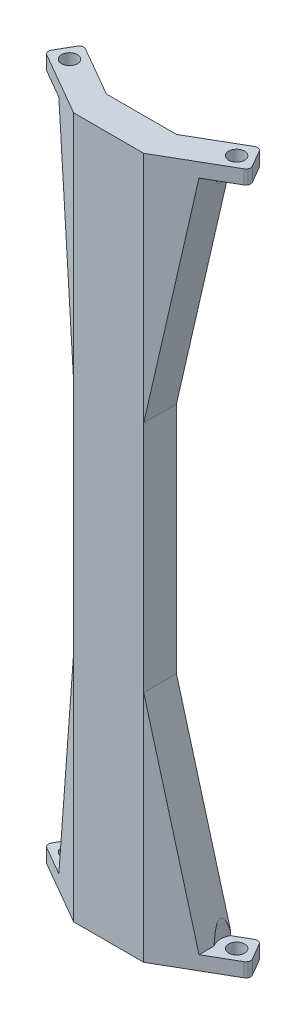
SolidWorks part; units mm, degrees
ref_plane "Front Plane" through (0, 0, 0) normal (0, 0, 1) x (1, 0, 0)
ref_plane "Top Plane" through (0, 0, 0) normal (0, 1, 0) x (1, 0, 0)
ref_plane "Right Plane" through (0, 0, 0) normal (1, 0, 0) x (0, 0, -1)
sketch "Sketch2" plane through (0, 0, 0) normal (0, 0, 1) x (1, 0, 0)
  line L1 (-7.5, -75) -> (7.5, -75)
  line L2 (-7.5, -75) -> (-7.5, 75)
  line L3 (-7.5, 75) -> (7.5, 75)
  line L4 (7.5, -75) -> (7.5, 75)
  line L5 (-7.5, -75) -> (7.5, 75) construction
  line L6 (-7.5, 75) -> (7.5, -75) construction
  point P0 (0, 0)
  dimension "D1" = 150
  dimension "D2" = 15
extrude "Boss-Extrude1" add sketch "Sketch2" along normal mid plane 7
sketch "Sketch3" plane through (0, -75, 0) normal (0, -1, 0) x (1, 0, 0)
  line L0 (-7.5, 3.5) -> (-22.0059, -4.875)
  line L1 (-22.0059, -4.875) -> (-18.9748, -10.125)
  line L2 (-18.9748, -10.125) -> (-7.5, -3.5)
  line L3 (7.5, 3.5) -> (22.0059, -4.875)
  line L4 (22.0059, -4.875) -> (18.9748, -10.125)
  line L5 (18.9748, -10.125) -> (7.5, -3.5)
  line L6 (-7.5, 3.5) -> (-7.5, -3.5) construction
  line L7 (7.5, 3.5) -> (7.5, -3.5) construction
  line L8 (-7.5, 3.5) -> (-7.5, -3.5)
  line L9 (7.5, 3.5) -> (7.5, -3.5)
  line L10 (-20.4904, -7.5) -> (-7.5, 0) construction
  dimension "D1" = 60
  dimension "D2" = 15
  dimension "D3" = 60
extrude "Boss-Extrude2" add sketch "Sketch3" against normal up to surface (150 mm away) up to face at (0, 75, 0)
sketch "Sketch5" plane through (0, 0, 3.5) normal (0, 0, 1) x (1, 0, 0)
  line L0 (-7.5, 25) -> (-7.5, -25)
  line L1 (-7.5, 75) -> (-7.5, -75) construction
  line L3 (-22.0059, 75) -> (-22.0059, -75) construction
  line L4 (-22.0059, -72) -> (-22.0059, 72)
  line L6 (0, -75) -> (0, 75) construction
  line L9 (-7.5, -75) -> (7.5, -75) construction
  line L10 (7.5, 75) -> (-7.5, 75) construction
  line L15 (-22.0059, 72) -> (-15.0059, 72)
  line L16 (-15.0059, 72) -> (-7.5, 25)
  line L17 (-22.0059, -72) -> (-15.0059, -72)
  line L18 (-15.0059, -72) -> (-7.5, -25)
  line L19 (-7.5, -75) -> (-22.0059, -75) construction
  line L20 (-22.0059, 75) -> (-7.5, 75) construction
  line L21 (22.0059, -72) -> (15.0059, -72)
  line L22 (22.0059, -72) -> (22.0059, 72)
  line L23 (22.0059, 72) -> (15.0059, 72)
  line L24 (15.0059, 72) -> (7.5, 25)
  line L25 (7.5, 25) -> (7.5, -25)
  line L26 (15.0059, -72) -> (7.5, -25)
  dimension "D1" = 50
  dimension "D2" = 50
  dimension "D3" = 7
  dimension "D4" = 7
  dimension "D5" = 3
  dimension "D6" = 3
extrude "Cut-Extrude1" cut sketch "Sketch5" against normal through all
sketch "Sketch6" plane through (0, -72, 0) normal (0, 1, 0) x (1, 0, 0)
  line L0 (17.8923, 6) -> (20.4904, 7.5) construction
  line L1 (22.0059, 4.875) -> (18.9748, 10.125) construction
  line L2 (-20.4904, 7.5) -> (-17.8923, 6) construction
  line L3 (-18.9748, 10.125) -> (-22.0059, 4.875) construction
  circle A0 centre (17.8923, 6) radius 1.7
  circle A1 centre (-17.8923, 6) radius 1.7
  dimension "D1" = 3.4
  dimension "D2" = 3
  dimension "D3" = 3
extrude "Cut-Extrude2" cut sketch "Sketch6" against normal up to next
fillet "Fillet2" radius 1 4 edges at (-18.9748, -73.5, -10.125) (-22.0059, -73.5, -4.875) (22.0059, -73.5, -4.875) (18.9748, -73.5, -10.125)
sketch "Sketch7" plane through (0, -72, 0) normal (0, 1, 0) x (1, 0, 0)
  line L0 (0, 3.5) -> (0, -3.5) construction
  line L1 (-7.5, 3.5) -> (7.5, 3.5) construction
  line L2 (-7.5, -3.5) -> (7.5, -3.5) construction
  circle A0 centre (-17.8923, 6) radius 1.7 construction
  circle A1 centre (-17.8923, 6) radius 1.7 construction
  circle A2 centre (-17.8923, 6) radius 3.5
  circle A3 centre (17.8923, 6) radius 1.7 construction
  circle A4 centre (17.8923, 6) radius 3.5
  dimension "D1" = 7
extrude "Cut-Extrude3" cut sketch "Sketch7" along normal up to next
mirror "Mirror1" about plane through (0, 0, 0) normal (0, 1, 0) of "Cut-Extrude3", "Cut-Extrude2", "Fillet2"
equation "\"`\"=10"
